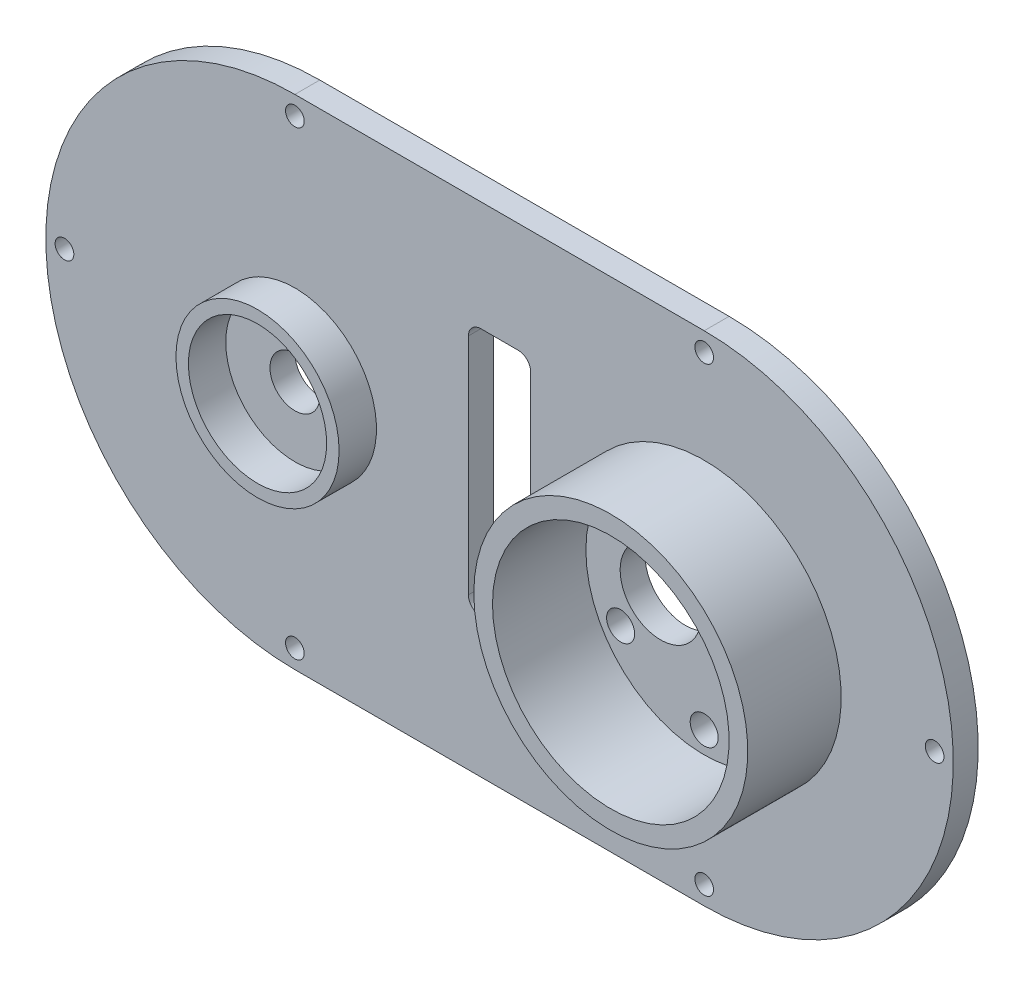
SolidWorks part; units mm, degrees
ref_plane "Front Plane" through (0, 0, 0) normal (0, 0, 1) x (1, 0, 0)
ref_plane "Top Plane" through (0, 0, 0) normal (0, 1, 0) x (1, 0, 0)
ref_plane "Right Plane" through (0, 0, 0) normal (1, 0, 0) x (0, 0, -1)
sketch "Sketch1" plane through (0, 0, 0) normal (0, 0, 1) x (1, 0, 0)
  line L0 (-14.3348, 37.6523) -> (51.3952, 37.6523)
  line L1 (51.3952, -42.3477) -> (-14.3348, -42.3477)
  arc A0 (51.3952, 37.6523) -> (51.3952, -42.3477) centre (51.3952, -2.3477) cw
  arc A1 (-14.3348, -42.3477) -> (-14.3348, 37.6523) centre (-14.3348, -2.3477) cw
extrude "Boss-Extrude1" add sketch "Sketch1" along normal blind 4
sketch "Sketch2" plane through (0, 0, 0) normal (0, 0, 1) x (1, 0, 0)
  circle A0 centre (44.3952, -2.3477) radius 6.5
  circle A1 centre (51.3952, 13.1523) radius 2.25
  circle A2 centre (64.8186, 5.4023) radius 2.25
  circle A3 centre (64.8186, -10.0977) radius 2.25
  circle A4 centre (51.3952, -17.8477) radius 2.25
  circle A5 centre (37.9718, -10.0977) radius 2.25
  circle A6 centre (37.9718, 5.4023) radius 2.25
  circle A7 centre (-14.3348, -2.3477) radius 4
  dimension "D1" = 13
  dimension "D2" = 4.5
  dimension "D3" = 8
extrude "Cut-Extrude1" cut sketch "Sketch2" along normal up to surface (4 mm away) from surface
sketch "Sketch3" plane through (0, 0, 0) normal (0, 0, 1) x (1, 0, 0)
  circle A0 centre (51.3952, -2.3477) radius 19
  circle A1 centre (51.3952, -2.3477) radius 22
  dimension "D1" = 3
  dimension "D2" = 38
extrude "Boss-Extrude2" add sketch "Sketch3" along normal blind 15 from surface at 4 starting at face at (-18.3348, -2.3477, 4)
sketch "Sketch4" plane through (0, 0, 0) normal (0, 0, 1) x (1, 0, 0)
  circle A0 centre (-14.3348, -2.3477) radius 11.1
  circle A1 centre (-14.3348, -2.3477) radius 13.1
  dimension "D1" = 22.2
  dimension "D2" = 2
extrude "Boss-Extrude3" add sketch "Sketch4" along normal blind 10
sketch "Sketch5" plane through (0, 0, 0) normal (0, 0, 1) x (1, 0, 0)
  line L4 (-14.3348, -39.3477) -> (51.3952, -39.3477)
  line L5 (51.3952, 34.6523) -> (-14.3348, 34.6523)
  line L6 (-14.3348, -39.3477) -> (51.3952, -39.3477) construction
  line L7 (51.3952, 34.6523) -> (-14.3348, 34.6523) construction
  circle A0 centre (88.3952, -2.3477) radius 1.5
  circle A1 centre (-51.3348, -2.3477) radius 1.5
  circle A2 centre (51.3952, 34.6523) radius 1.5
  circle A3 centre (51.3952, -39.3477) radius 1.5
  arc A4 (-14.3348, 34.6523) -> (-14.3348, -39.3477) centre (-14.3348, -2.3477) ccw
  arc A5 (51.3952, -39.3477) -> (51.3952, 34.6523) centre (51.3952, -2.3477) ccw
  arc A6 (-14.3348, 34.6523) -> (-14.3348, -39.3477) centre (-14.3348, -2.3477) ccw construction
  arc A7 (51.3952, -39.3477) -> (51.3952, 34.6523) centre (51.3952, -2.3477) ccw construction
  circle A8 centre (-14.3348, -39.3477) radius 1.5
  circle A9 centre (-14.3348, 34.6523) radius 1.5
  dimension "D2" = 3
  dimension "D1" = 3
extrude "Cut-Extrude2" cut sketch "Sketch5" along normal through all
sketch "Sketch6" plane through (0, 0, 0) normal (0, 0, 1) x (1, 0, 0)
  line L5 (0, 0) -> (18.5302, 0) construction
  line L7 (51.3952, 37.6523) -> (-14.3348, 37.6523) construction
  line L8 (18.5302, 37.6523) -> (18.5302, -33.6377) construction
  line L9 (13.5302, -20) -> (23.5302, -20)
  line L10 (13.5302, -20) -> (13.5302, 20)
  line L11 (13.5302, 20) -> (23.5302, 20)
  line L12 (23.5302, -20) -> (23.5302, 20)
  line L13 (13.5302, -20) -> (23.5302, 20) construction
  line L14 (13.5302, 20) -> (23.5302, -20) construction
  dimension "D1" = 40
  dimension "D2" = 10
extrude "Cut-Extrude3" cut sketch "Sketch6" along normal through all
fillet "Fillet1" radius 2 4 edges at (23.5302, -20, 2) (13.5302, -20, 2) (23.5302, 20, 2) (13.5302, 20, 2)
